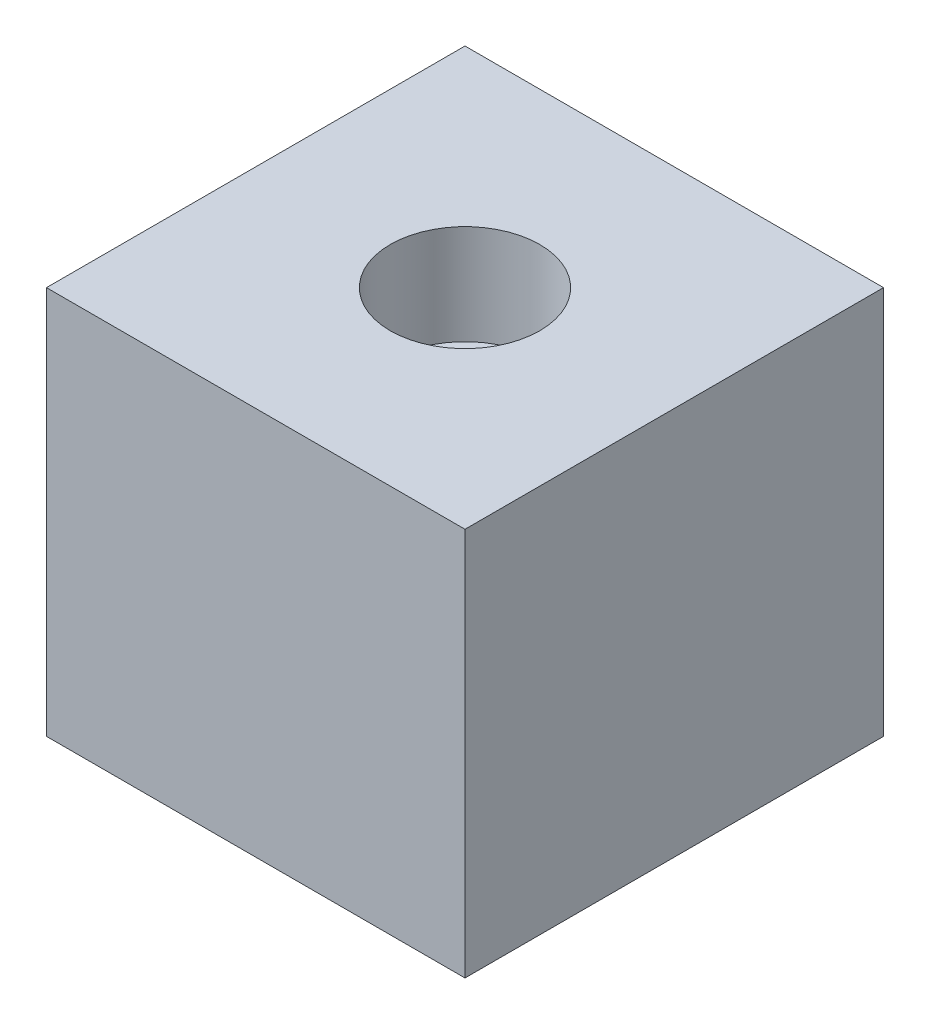
SolidWorks part; units mm, degrees
ref_plane "Plan de face" through (0, 0, 0) normal (0, 0, 1) x (1, 0, 0)
ref_plane "Plan de dessus" through (0, 0, 0) normal (0, 1, 0) x (1, 0, 0)
ref_plane "Plan de droite" through (0, 0, 0) normal (1, 0, 0) x (0, 0, -1)
sketch "Esquisse1" plane through (0, 0, 0) normal (0, 1, 0) x (1, 0, 0)
  line L1 (-21, -21) -> (21, -21)
  line L2 (-21, -21) -> (-21, 21)
  line L3 (-21, 21) -> (21, 21)
  line L4 (21, -21) -> (21, 21)
  line L5 (-21, -21) -> (21, 21) construction
  line L6 (-21, 21) -> (21, -21) construction
  point P0 (0, 0)
  dimension "D1" = 42
  dimension "D2" = 42
extrude "Boss.-Extru.1" add sketch "Esquisse1" along normal blind 39
ref_plane "Plan1" through (0, 39, 0) normal (0, 1, 0) x (1, 0, 0)
sketch "Esquisse3" plane through (0, 39, 0) normal (0, 1, 0) x (1, 0, 0)
  circle A0 centre (0, 0) radius 7.5
  dimension "D1" = 15
extrude "Enlèv. mat.-Extru.2" cut sketch "Esquisse3" against normal blind 10
